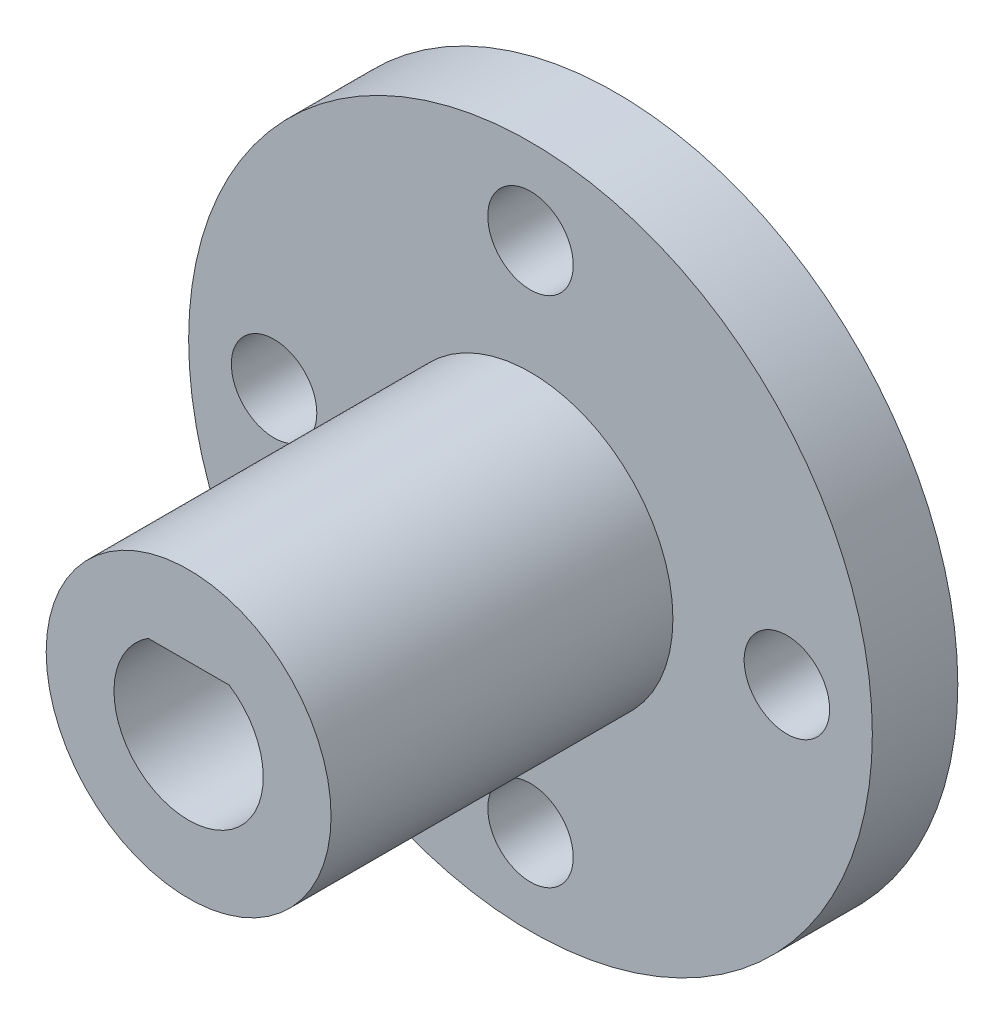
SolidWorks part; units mm, degrees
ref_plane "前视基准面" through (0, 0, 0) normal (0, 0, 1) x (1, 0, 0)
ref_plane "上视基准面" through (0, 0, 0) normal (0, 1, 0) x (1, 0, 0)
ref_plane "右视基准面" through (0, 0, 0) normal (1, 0, 0) x (0, 0, -1)
sketch "Sketch1" plane through (0, 0, 0) normal (0, 0, 1) x (1, 0, 0)
  circle A0 centre (0, 0) radius 12
extrude "Boss-Extrude1" add sketch "Sketch1" along normal blind 3
sketch "Sketch2" plane through (0, 0, 0) normal (0, 0, 1) x (1, 0, 0)
  circle A0 centre (0, 0) radius 5
extrude "Boss-Extrude2" add sketch "Sketch2" along normal blind 15
sketch "Sketch3" plane through (0, 0, 0) normal (0, 0, 1) x (1, 0, 0)
  line L1 (-0.0651, 2.2008) -> (1.4216, 2.2008)
  line L3 (-0.0651, 2.2008) -> (-1.4216, 2.2008)
  arc A1 (-1.4216, 2.2008) -> (1.4216, 2.2008) centre (0, 0) ccw
extrude "Cut-Extrude1" cut sketch "Sketch3" along normal blind 15
sketch "Sketch4" plane through (0, 0, 0) normal (0, 0, 1) x (1, 0, 0)
  circle A0 centre (-9, 0) radius 1.5
  circle A1 centre (0, 9) radius 1.5
  circle A2 centre (9, 0) radius 1.5
  circle A3 centre (0, -9) radius 1.5
  point P12 (0, 0)
  dimension "D1" = 4
extrude "Cut-Extrude2" cut sketch "Sketch4" along normal blind 5
